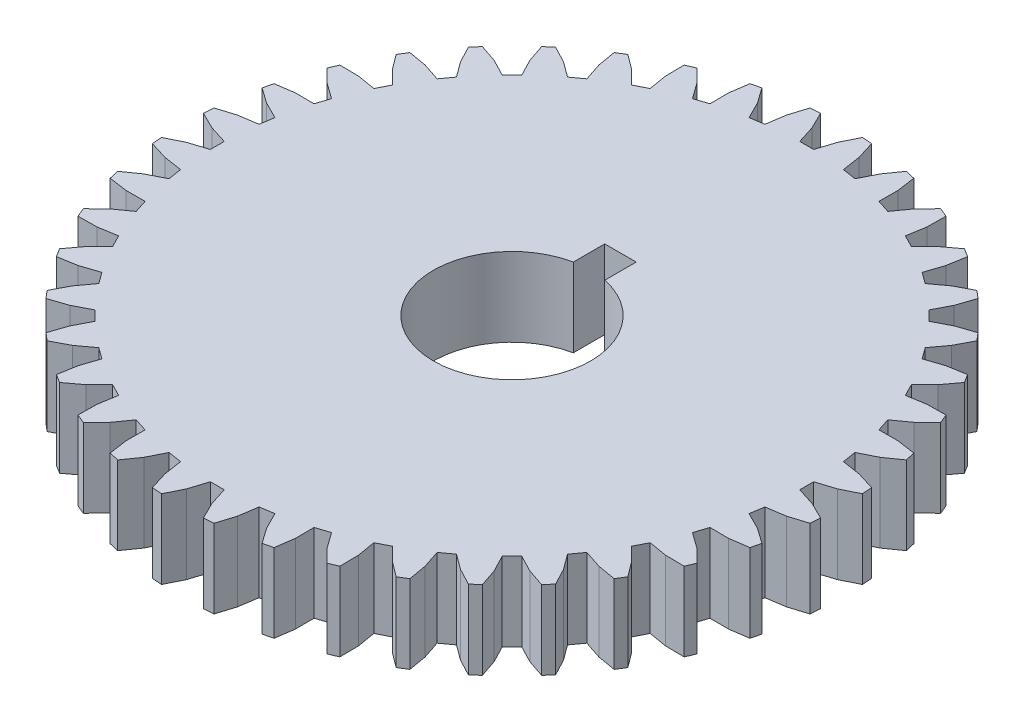
SolidWorks part; units mm, degrees
ref_plane "前视基准面" through (0, 0, 0) normal (0, 0, 1) x (1, 0, 0)
ref_plane "上视基准面" through (0, 0, 0) normal (0, 1, 0) x (1, 0, 0)
ref_plane "右视基准面" through (0, 0, 0) normal (1, 0, 0) x (0, 0, -1)
sketch "草图1" plane through (0, 0, 0) normal (0, 1, 0) x (1, 0, 0)
  line L0 (6.7941, 36.7362) -> (6.7941, 40.7362)
  line L1 (6.7941, 40.7362) -> (2.7941, 40.7362)
  line L2 (2.7941, 40.7362) -> (2.7941, 36.7362)
  line L3 (15.5391, 62.8649) -> (17.2183, 62.3193)
  line L4 (17.2183, 62.3193) -> (18.612, 64.2639)
  line L5 (18.612, 64.2639) -> (20.2802, 65.979)
  line L6 (20.2802, 65.979) -> (21.4497, 65.4946)
  line L7 (21.4497, 65.4946) -> (21.4165, 63.1023)
  line L8 (21.4165, 63.1023) -> (21.0269, 60.7417)
  line L9 (26.8691, 60.0567) -> (26.1151, 57.7861)
  line L10 (27.2761, 62.4144) -> (26.8691, 60.0567)
  line L11 (26.1969, 63.0758) -> (27.2761, 62.4144)
  line L12 (24.2809, 61.6428) -> (26.1969, 63.0758)
  line L13 (22.6001, 59.9401) -> (24.2809, 61.6428)
  line L14 (21.0269, 60.7417) -> (22.6001, 59.9401)
  line L15 (31.7782, 56.1957) -> (30.6783, 54.071)
  line L16 (32.549, 58.4607) -> (31.7782, 56.1957)
  line L17 (31.5865, 59.2827) -> (32.549, 58.4607)
  line L18 (29.47, 58.1671) -> (31.5865, 59.2827)
  line L19 (27.5435, 56.7483) -> (29.47, 58.1671)
  line L20 (26.1151, 57.7861) -> (27.5435, 56.7483)
  line L21 (36.0229, 51.6142) -> (34.6041, 49.6877)
  line L22 (37.1385, 53.7307) -> (36.0229, 51.6142)
  line L23 (36.3164, 54.6933) -> (37.1385, 53.7307)
  line L24 (34.0515, 53.9224) -> (36.3164, 54.6933)
  line L25 (31.9267, 52.8225) -> (34.0515, 53.9224)
  line L26 (30.6783, 54.071) -> (31.9267, 52.8225)
  line L27 (39.4985, 46.4252) -> (37.7959, 44.7443)
  line L28 (40.9316, 48.3411) -> (39.4985, 46.4252)
  line L29 (40.2702, 49.4204) -> (40.9316, 48.3411)
  line L30 (37.9125, 49.0134) -> (40.2702, 49.4204)
  line L31 (35.6419, 48.2593) -> (37.9125, 49.0134)
  line L32 (34.6041, 49.6877) -> (35.6419, 48.2593)
  line L33 (42.1197, 40.7563) -> (40.175, 39.3625)
  line L34 (43.8348, 42.4244) -> (42.1197, 40.7563)
  line L35 (43.3504, 43.5939) -> (43.8348, 42.4244)
  line L36 (40.9581, 43.5607) -> (43.3504, 43.5939)
  line L37 (38.5974, 43.1712) -> (40.9581, 43.5607)
  line L38 (37.7959, 44.7443) -> (38.5974, 43.1712)
  line L39 (43.8218, 34.7471) -> (41.683, 33.6747)
  line L40 (45.7767, 36.1265) -> (43.8218, 34.7471)
  line L41 (45.4812, 37.3573) -> (45.7767, 36.1265)
  line L42 (43.1131, 37.6988) -> (45.4812, 37.3573)
  line L43 (40.7206, 37.6833) -> (43.1131, 37.6988)
  line L44 (40.175, 39.3625) -> (40.7206, 37.6833)
  line L45 (44.5628, 28.5457) -> (42.2827, 27.8211)
  line L46 (46.7095, 29.6022) -> (44.5628, 28.5457)
  line L47 (46.6102, 30.8641) -> (46.7095, 29.6022)
  line L48 (44.3247, 31.5719) -> (46.6102, 30.8641)
  line L49 (41.9592, 31.9308) -> (44.3247, 31.5719)
  line L50 (41.683, 33.6747) -> (41.9592, 31.9308)
  line L51 (44.3247, 22.3047) -> (41.9592, 21.9457)
  line L52 (46.6102, 23.0124) -> (44.3247, 22.3047)
  line L53 (46.7095, 24.2743) -> (46.6102, 23.0124)
  line L54 (44.5628, 25.3309) -> (46.7095, 24.2743)
  line L55 (42.2827, 26.0555) -> (44.5628, 25.3309)
  line L56 (42.2827, 27.8211) -> (42.2827, 26.0555)
  line L57 (43.1131, 16.1778) -> (40.7206, 16.1933)
  line L58 (45.4812, 16.5193) -> (43.1131, 16.1778)
  line L59 (45.7767, 17.7501) -> (45.4812, 16.5193)
  line L60 (43.8218, 19.1294) -> (45.7767, 17.7501)
  line L61 (41.683, 20.2018) -> (43.8218, 19.1294)
  line L62 (41.9592, 21.9457) -> (41.683, 20.2018)
  line L63 (40.9581, 10.3159) -> (38.5974, 10.7054)
  line L64 (43.3504, 10.2827) -> (40.9581, 10.3159)
  line L65 (43.8348, 11.4521) -> (43.3504, 10.2827)
  line L66 (42.1197, 13.1203) -> (43.8348, 11.4521)
  line L67 (40.175, 14.5141) -> (42.1197, 13.1203)
  line L68 (40.7206, 16.1933) -> (40.175, 14.5141)
  line L69 (37.9125, 4.8632) -> (35.6419, 5.6172)
  line L70 (40.2702, 4.4562) -> (37.9125, 4.8632)
  line L71 (40.9316, 5.5355) -> (40.2702, 4.4562)
  line L72 (39.4985, 7.4514) -> (40.9316, 5.5355)
  line L73 (37.7959, 9.1322) -> (39.4985, 7.4514)
  line L74 (38.5974, 10.7054) -> (37.7959, 9.1322)
  line L75 (34.0515, -0.0459) -> (31.9267, 1.0541)
  line L76 (36.3164, -0.8167) -> (34.0515, -0.0459)
  line L77 (37.1385, 0.1458) -> (36.3164, -0.8167)
  line L78 (36.0229, 2.2623) -> (37.1385, 0.1458)
  line L79 (34.6041, 4.1888) -> (36.0229, 2.2623)
  line L80 (35.6419, 5.6172) -> (34.6041, 4.1888)
  line L81 (29.47, -4.2905) -> (27.5435, -2.8717)
  line L82 (31.5865, -5.4062) -> (29.47, -4.2905)
  line L83 (32.549, -4.5841) -> (31.5865, -5.4062)
  line L84 (31.7782, -2.3191) -> (32.549, -4.5841)
  line L85 (30.6783, -0.1944) -> (31.7782, -2.3191)
  line L86 (31.9267, 1.0541) -> (30.6783, -0.1944)
  line L87 (24.2809, -7.7662) -> (22.6001, -6.0635)
  line L88 (26.1969, -9.1992) -> (24.2809, -7.7662)
  line L89 (27.2761, -8.5378) -> (26.1969, -9.1992)
  line L90 (26.8691, -6.1802) -> (27.2761, -8.5378)
  line L91 (26.1151, -3.9095) -> (26.8691, -6.1802)
  line L92 (27.5435, -2.8717) -> (26.1151, -3.9095)
  line L93 (18.612, -10.3874) -> (17.2183, -8.4427)
  line L94 (20.2802, -12.1025) -> (18.612, -10.3874)
  line L95 (21.4497, -11.6181) -> (20.2802, -12.1025)
  line L96 (21.4165, -9.2257) -> (21.4497, -11.6181)
  line L97 (21.0269, -6.8651) -> (21.4165, -9.2257)
  line L98 (22.6001, -6.0635) -> (21.0269, -6.8651)
  line L99 (12.6029, -12.0894) -> (11.5305, -9.9507)
  line L100 (13.9822, -14.0444) -> (12.6029, -12.0894)
  line L101 (15.2131, -13.7489) -> (13.9822, -14.0444)
  line L102 (15.5545, -11.3808) -> (15.2131, -13.7489)
  line L103 (15.5391, -8.9883) -> (15.5545, -11.3808)
  line L104 (17.2183, -8.4427) -> (15.5391, -8.9883)
  line L105 (6.4015, -12.8305) -> (5.6769, -10.5503)
  line L106 (7.458, -14.9771) -> (6.4015, -12.8305)
  line L107 (8.7199, -14.8778) -> (7.458, -14.9771)
  line L108 (9.4276, -12.5923) -> (8.7199, -14.8778)
  line L109 (9.7866, -10.2269) -> (9.4276, -12.5923)
  line L110 (11.5305, -9.9507) -> (9.7866, -10.2269)
  line L111 (0.1605, -12.5923) -> (-0.1985, -10.2269)
  line L112 (0.8682, -14.8778) -> (0.1605, -12.5923)
  line L113 (2.1301, -14.9771) -> (0.8682, -14.8778)
  line L114 (3.1866, -12.8305) -> (2.1301, -14.9771)
  line L115 (3.9112, -10.5503) -> (3.1866, -12.8305)
  line L116 (5.6769, -10.5503) -> (3.9112, -10.5503)
  line L117 (-5.9664, -11.3808) -> (-5.951, -8.9883)
  line L118 (-5.625, -13.7489) -> (-5.9664, -11.3808)
  line L119 (-4.3941, -14.0444) -> (-5.625, -13.7489)
  line L120 (-3.0148, -12.0894) -> (-4.3941, -14.0444)
  line L121 (-1.9424, -9.9507) -> (-3.0148, -12.0894)
  line L122 (-0.1985, -10.2269) -> (-1.9424, -9.9507)
  line L123 (-11.8284, -9.2257) -> (-11.4388, -6.8651)
  line L124 (-11.8616, -11.6181) -> (-11.8284, -9.2257)
  line L125 (-10.6921, -12.1025) -> (-11.8616, -11.6181)
  line L126 (-9.0239, -10.3874) -> (-10.6921, -12.1025)
  line L127 (-7.6302, -8.4427) -> (-9.0239, -10.3874)
  line L128 (-5.951, -8.9883) -> (-7.6302, -8.4427)
  line L129 (-17.281, -6.1802) -> (-16.527, -3.9095)
  line L130 (-17.688, -8.5378) -> (-17.281, -6.1802)
  line L131 (-16.6088, -9.1992) -> (-17.688, -8.5378)
  line L132 (-14.6928, -7.7662) -> (-16.6088, -9.1992)
  line L133 (-13.012, -6.0635) -> (-14.6928, -7.7662)
  line L134 (-11.4388, -6.8651) -> (-13.012, -6.0635)
  line L135 (-22.1901, -2.3191) -> (-21.0902, -0.1944)
  line L136 (-22.9609, -4.5841) -> (-22.1901, -2.3191)
  line L137 (-21.9984, -5.4062) -> (-22.9609, -4.5841)
  line L138 (-19.8819, -4.2905) -> (-21.9984, -5.4062)
  line L139 (-17.9554, -2.8717) -> (-19.8819, -4.2905)
  line L140 (-16.527, -3.9095) -> (-17.9554, -2.8717)
  line L141 (-26.4348, 2.2623) -> (-25.016, 4.1888)
  line L142 (-27.5504, 0.1458) -> (-26.4348, 2.2623)
  line L143 (-26.7283, -0.8167) -> (-27.5504, 0.1458)
  line L144 (-24.4634, -0.0459) -> (-26.7283, -0.8167)
  line L145 (-22.3386, 1.0541) -> (-24.4634, -0.0459)
  line L146 (-21.0902, -0.1944) -> (-22.3386, 1.0541)
  line L147 (-29.9104, 7.4514) -> (-28.2078, 9.1322)
  line L148 (-31.3435, 5.5355) -> (-29.9104, 7.4514)
  line L149 (-30.6821, 4.4562) -> (-31.3435, 5.5355)
  line L150 (-28.3244, 4.8632) -> (-30.6821, 4.4562)
  line L151 (-26.0538, 5.6172) -> (-28.3244, 4.8632)
  line L152 (-25.016, 4.1888) -> (-26.0538, 5.6172)
  line L153 (-32.5316, 13.1203) -> (-30.5869, 14.5141)
  line L154 (-34.2467, 11.4521) -> (-32.5316, 13.1203)
  line L155 (-33.7623, 10.2827) -> (-34.2467, 11.4521)
  line L156 (-31.37, 10.3159) -> (-33.7623, 10.2827)
  line L157 (-29.0093, 10.7054) -> (-31.37, 10.3159)
  line L158 (-28.2078, 9.1322) -> (-29.0093, 10.7054)
  line L159 (-34.2337, 19.1294) -> (-32.0949, 20.2018)
  line L160 (-36.1886, 17.7501) -> (-34.2337, 19.1294)
  line L161 (-35.8931, 16.5193) -> (-36.1886, 17.7501)
  line L162 (-33.525, 16.1778) -> (-35.8931, 16.5193)
  line L163 (-31.1325, 16.1933) -> (-33.525, 16.1778)
  line L164 (-30.5869, 14.5141) -> (-31.1325, 16.1933)
  line L165 (-34.9747, 25.3309) -> (-32.6946, 26.0555)
  line L166 (-37.1214, 24.2743) -> (-34.9747, 25.3309)
  line L167 (-37.0221, 23.0124) -> (-37.1214, 24.2743)
  line L168 (-34.7366, 22.3047) -> (-37.0221, 23.0124)
  line L169 (-32.3711, 21.9457) -> (-34.7366, 22.3047)
  line L170 (-32.0949, 20.2018) -> (-32.3711, 21.9457)
  line L171 (-34.7366, 31.5719) -> (-32.3711, 31.9308)
  line L172 (-37.0221, 30.8641) -> (-34.7366, 31.5719)
  line L173 (-37.1214, 29.6022) -> (-37.0221, 30.8641)
  line L174 (-34.9747, 28.5457) -> (-37.1214, 29.6022)
  line L175 (-32.6946, 27.8211) -> (-34.9747, 28.5457)
  line L176 (-32.6946, 26.0555) -> (-32.6946, 27.8211)
  line L177 (-33.525, 37.6988) -> (-31.1325, 37.6833)
  line L178 (-35.8931, 37.3573) -> (-33.525, 37.6988)
  line L179 (-36.1886, 36.1265) -> (-35.8931, 37.3573)
  line L180 (-34.2337, 34.7471) -> (-36.1886, 36.1265)
  line L181 (-32.0949, 33.6747) -> (-34.2337, 34.7471)
  line L182 (-32.3711, 31.9308) -> (-32.0949, 33.6747)
  line L183 (-31.37, 43.5607) -> (-29.0093, 43.1712)
  line L184 (-33.7623, 43.5939) -> (-31.37, 43.5607)
  line L185 (-34.2467, 42.4244) -> (-33.7623, 43.5939)
  line L186 (-32.5316, 40.7563) -> (-34.2467, 42.4244)
  line L187 (-30.5869, 39.3625) -> (-32.5316, 40.7563)
  line L188 (-31.1325, 37.6833) -> (-30.5869, 39.3625)
  line L189 (-28.3244, 49.0134) -> (-26.0538, 48.2593)
  line L190 (-30.6821, 49.4204) -> (-28.3244, 49.0134)
  line L191 (-31.3435, 48.3411) -> (-30.6821, 49.4204)
  line L192 (-29.9104, 46.4252) -> (-31.3435, 48.3411)
  line L193 (-28.2078, 44.7443) -> (-29.9104, 46.4252)
  line L194 (-29.0093, 43.1712) -> (-28.2078, 44.7443)
  line L195 (-24.4634, 53.9224) -> (-22.3386, 52.8225)
  line L196 (-26.7283, 54.6933) -> (-24.4634, 53.9224)
  line L197 (-27.5504, 53.7307) -> (-26.7283, 54.6933)
  line L198 (-26.4348, 51.6142) -> (-27.5504, 53.7307)
  line L199 (-25.016, 49.6877) -> (-26.4348, 51.6142)
  line L200 (-26.0538, 48.2593) -> (-25.016, 49.6877)
  line L201 (-19.8819, 58.1671) -> (-17.9554, 56.7483)
  line L202 (-21.9984, 59.2827) -> (-19.8819, 58.1671)
  line L203 (-22.9609, 58.4607) -> (-21.9984, 59.2827)
  line L204 (-22.1901, 56.1957) -> (-22.9609, 58.4607)
  line L205 (-21.0902, 54.071) -> (-22.1901, 56.1957)
  line L206 (-22.3386, 52.8225) -> (-21.0902, 54.071)
  line L207 (-14.6928, 61.6428) -> (-13.012, 59.9401)
  line L208 (-16.6088, 63.0758) -> (-14.6928, 61.6428)
  line L209 (-17.688, 62.4144) -> (-16.6088, 63.0758)
  line L210 (-17.281, 60.0567) -> (-17.688, 62.4144)
  line L211 (-16.527, 57.7861) -> (-17.281, 60.0567)
  line L212 (-17.9554, 56.7483) -> (-16.527, 57.7861)
  line L213 (-9.0239, 64.2639) -> (-7.6302, 62.3193)
  line L214 (-10.6921, 65.979) -> (-9.0239, 64.2639)
  line L215 (-11.8616, 65.4946) -> (-10.6921, 65.979)
  line L216 (-11.8284, 63.1023) -> (-11.8616, 65.4946)
  line L217 (-11.4388, 60.7417) -> (-11.8284, 63.1023)
  line L218 (-13.012, 59.9401) -> (-11.4388, 60.7417)
  line L219 (-3.0148, 65.966) -> (-1.9424, 63.8272)
  line L220 (-4.3941, 67.9209) -> (-3.0148, 65.966)
  line L221 (-5.625, 67.6254) -> (-4.3941, 67.9209)
  line L222 (-5.9664, 65.2574) -> (-5.625, 67.6254)
  line L223 (-5.951, 62.8649) -> (-5.9664, 65.2574)
  line L224 (-7.6302, 62.3193) -> (-5.951, 62.8649)
  line L225 (3.1866, 66.7071) -> (3.9112, 64.4269)
  line L226 (2.1301, 68.8537) -> (3.1866, 66.7071)
  line L227 (0.8682, 68.7544) -> (2.1301, 68.8537)
  line L228 (0.1605, 66.4689) -> (0.8682, 68.7544)
  line L229 (-0.1985, 64.1034) -> (0.1605, 66.4689)
  line L230 (-1.9424, 63.8272) -> (-0.1985, 64.1034)
  line L231 (9.4276, 66.4689) -> (9.7866, 64.1034)
  line L232 (8.7199, 68.7544) -> (9.4276, 66.4689)
  line L233 (7.458, 68.8537) -> (8.7199, 68.7544)
  line L234 (6.4015, 66.7071) -> (7.458, 68.8537)
  line L235 (5.6769, 64.4269) -> (6.4015, 66.7071)
  line L236 (3.9112, 64.4269) -> (5.6769, 64.4269)
  line L237 (15.5545, 65.2574) -> (15.5391, 62.8649)
  line L238 (15.2131, 67.6254) -> (15.5545, 65.2574)
  line L239 (13.9822, 67.9209) -> (15.2131, 67.6254)
  line L240 (12.6029, 65.966) -> (13.9822, 67.9209)
  line L241 (11.5305, 63.8272) -> (12.6029, 65.966)
  line L242 (9.7866, 64.1034) -> (11.5305, 63.8272)
  arc A0 (2.7941, 36.7362) -> (6.7941, 36.7362) centre (4.7941, 26.9383) ccw
  point P245 (4.7941, 26.9383)
extrude "凸台-拉伸1" add sketch "草图1" along normal blind 10
